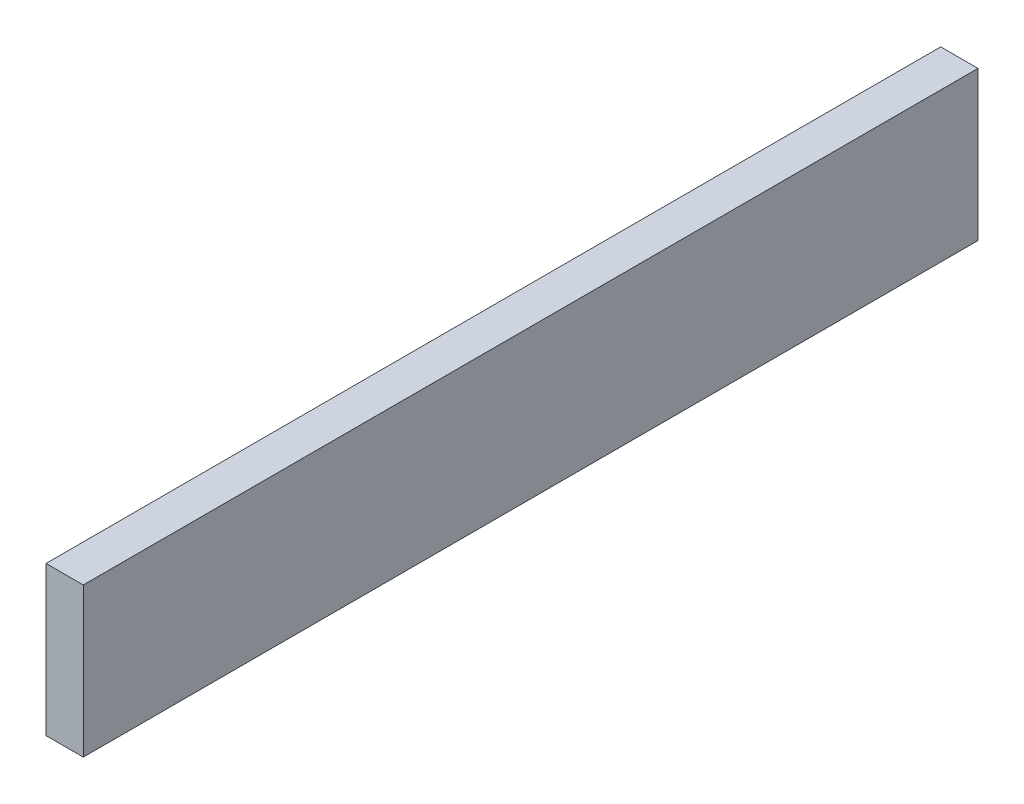
SolidWorks part; units mm, degrees
ref_plane "Front Plane" through (0, 0, 0) normal (0, 0, 1) x (1, 0, 0)
ref_plane "Top Plane" through (0, 0, 0) normal (0, 1, 0) x (1, 0, 0)
ref_plane "Right Plane" through (0, 0, 0) normal (1, 0, 0) x (0, 0, -1)
sketch "Sketch1" plane through (0, 0, 0) normal (1, 0, 0) x (0, 0, -1)
  line L1 (38.1, -6.35) -> (-38.1, -6.35)
  line L2 (38.1, -6.35) -> (38.1, 6.35)
  line L3 (38.1, 6.35) -> (-38.1, 6.35)
  line L4 (-38.1, -6.35) -> (-38.1, 6.35)
  line L5 (38.1, -6.35) -> (-38.1, 6.35) construction
  line L6 (38.1, 6.35) -> (-38.1, -6.35) construction
  point P0 (0, 0)
  dimension "D1" = 12.7
  dimension "D2" = 76.2
extrude "Boss-Extrude1" add sketch "Sketch1" along normal blind 3.175
